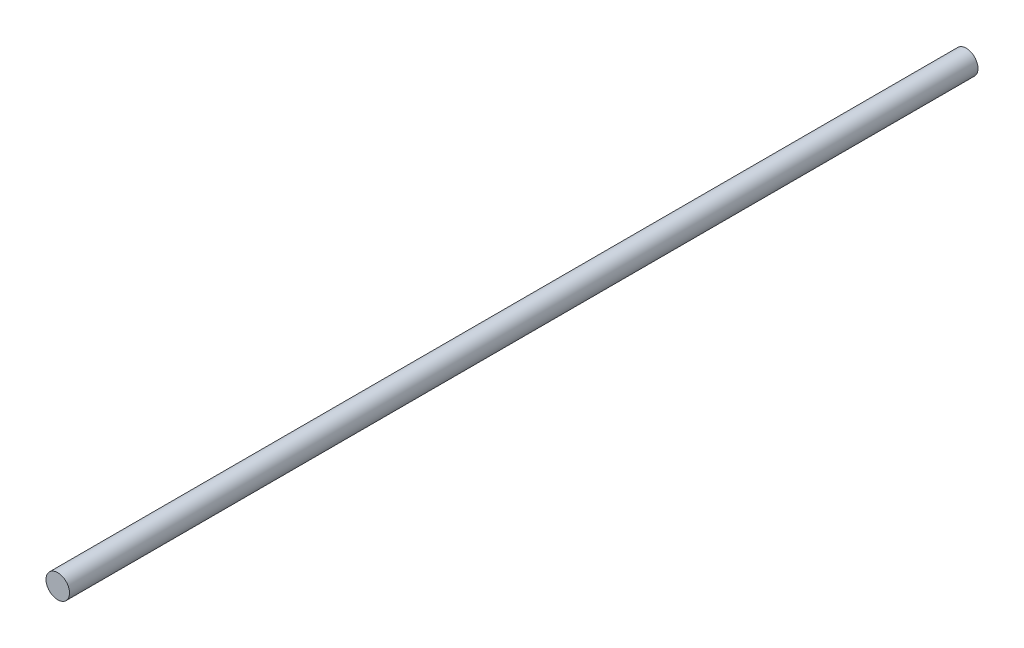
SolidWorks part; units mm, degrees
material "Hexcel AS4C (3000 filamentos)"
ref_plane "Alzado" through (0, 0, 0) normal (0, 0, 1) x (1, 0, 0)
ref_plane "Planta" through (0, 0, 0) normal (0, 1, 0) x (1, 0, 0)
ref_plane "Vista lateral" through (0, 0, 0) normal (1, 0, 0) x (0, 0, -1)
sketch "Croquis1" plane through (0, 0, 0) normal (0, 0, 1) x (1, 0, 0)
  circle A0 centre (0, 0) radius 3.175
  dimension "D1" = 6.35
extrude "Saliente-Extruir1" add sketch "Croquis1" along normal blind 245
